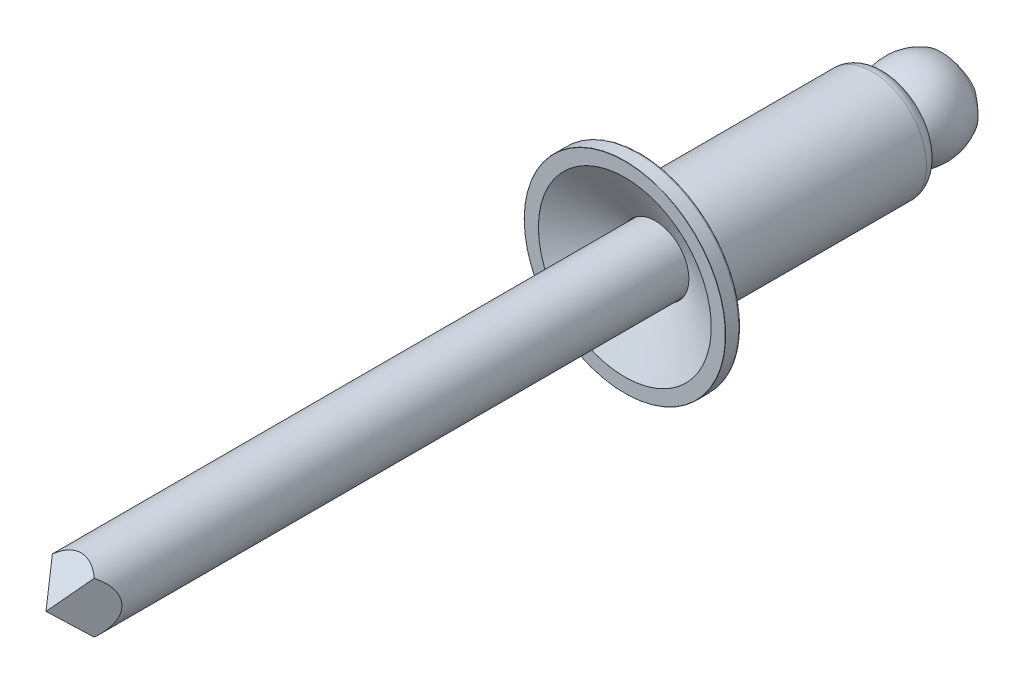
SolidWorks part; units mm, degrees
ref_plane "Front" through (0, 0, 0) normal (0, 0, 1) x (1, 0, 0)
ref_plane "Top" through (0, 0, 0) normal (0, 1, 0) x (1, 0, 0)
ref_plane "Right" through (0, 0, 0) normal (1, 0, 0) x (0, 0, -1)
sketch "Sketch1" plane through (0, 0, 0) normal (1, 0, 0) x (0, 0, -1)
  line L0 (-27.2034, 0) -> (-1.8034, 0) construction
  line L1 (-1.8034, 0) -> (0, 0) construction
  line L2 (0, 0) -> (9.6266, 0) construction
  line L3 (9.6266, 0) -> (12.4841, 0) construction
  line L4 (-1.1768, 4.4196) -> (0, 2.3813) construction
  line L5 (0, -2.3813) -> (-1.1768, -4.4196) construction
  line L8 (0, 4.4196) -> (0, -4.4196) construction
  line L9 (9.6266, 2.3813) -> (9.6266, -2.3813) construction
  point P7 (-1.8034, 4.4196)
  point P10 (-1.8034, -4.4196)
  point P25 (-1.8034, 1.4478)
  dimension "Head Height" = 1.8034
  dimension "D5" = 2.8575
  dimension "Diameter" = 4.7625
  dimension "Head Diameter" = 8.8392
  dimension "Countersink Angle" = 120
  dimension "Mandrel OD" = 2.8956
  dimension "Length" = 11.43
sketch "Sketch2" plane through (0, 0, 0) normal (1, 0, 0) x (0, 0, -1)
  line L0 (-27.2034, 0) -> (-27.2034, 1.4478)
  line L1 (-1.8034, 4.4196) -> (-1.8034, 3.793)
  line L2 (-1.8034, 4.4196) -> (-1.1768, 4.4196)
  line L3 (0, 0) -> (0, 4.4196) construction
  line L4 (-1.8034, 0) -> (-1.8034, 0.7239) construction
  line L5 (9.0551, 2.3812) -> (0, 2.3812)
  line L6 (9.6266, 2.3813) -> (9.6266, -2.3813) construction
  line L7 (-1.1768, 4.4196) -> (0, 2.3813) construction
  line L8 (0, 0) -> (9.6266, 0) construction
  line L9 (9.6266, 1.905) -> (12.4841, 1.905) construction
  line L10 (9.6266, 1.6669) -> (9.4075, 1.4478)
  line L11 (9.4075, 1.4478) -> (9.6266, 1.4478)
  line L12 (-27.2034, 0) -> (9.6266, 0)
  line L13 (-1.8034, 1.4478) -> (-1.8034, 0) construction
  line L14 (9.6266, 1.4478) -> (9.6266, 1.905) construction
  line L15 (12.4841, 0) -> (12.4841, 1.905) construction
  line L16 (12.076, 1.6193) -> (12.4841, 1.905) construction
  line L17 (-0.464, 1.4732) -> (4.5275, 1.4732)
  line L18 (12.076, 1.6193) -> (12.076, 0)
  line L19 (-1.1768, 4.4196) -> (0, 2.3812)
  line L20 (-1.8034, 1.4478) -> (-27.2034, 1.4478)
  line L21 (4.5275, 1.4732) -> (4.5275, 1.4478)
  line L22 (4.5275, 1.4478) -> (-1.8034, 1.4478)
  line L23 (12.076, 0) -> (9.6266, 0)
  line L24 (-1.8034, 3.793) -> (-0.464, 1.4732)
  arc A0 (9.0551, 2.3812) -> (9.6266, 1.6669) centre (9.0551, 1.7955) cw
  arc A1 (9.6266, 1.4478) -> (12.076, 1.6193) centre (10.9819, -0.3324) cw
  arc A2 (12.076, 1.6193) -> (12.4841, 0) centre (9.0676, 0) cw construction
  point P39 (4.5275, 2.3812)
  dimension "D1" = 0.5715
  dimension "D2" = 45
  dimension "D3" = 3.3337
  dimension "D4" = 3.81
  dimension "D5" = 35
  dimension "D6" = 3.2385
  dimension "D7" = 0.0254
revolve "Revolve1" add sketch "Sketch2" angle 360 about L12
sketch "Sketch3" plane through (0, 0, 0) normal (0, 1, 0) x (1, 0, 0)
  line L0 (0, -27.2034) -> (1.651, -25.0518)
  line L1 (-1.4478, -27.2034) -> (1.4478, -27.2034) construction
  line L3 (0, -27.2034) -> (0, -27.7114) construction
  line L4 (0, -27.2034) -> (-1.651, -25.0518)
  line L5 (-1.651, -25.0518) -> (-1.651, -27.7114)
  line L6 (-1.651, -27.7114) -> (1.651, -27.7114)
  line L7 (1.651, -27.7114) -> (1.651, -25.0518)
  dimension "D1" = 75
  dimension "D2" = 0.2032
  dimension "D3" = 0.508
extrude "Cut-Extrude1" cut sketch "Sketch3" against normal through all both and the other way through all
sketch "Sketch5" plane through (0, 0, 0) normal (1, 0, 0) x (0, 0, -1)
  line L0 (-27.2034, 0) -> (-25.3166, 1.7653)
  line L1 (-27.2034, -1.4478) -> (-27.2034, 1.4478) construction
  line L2 (-25.3166, 1.7653) -> (-27.5209, 1.7653)
  line L3 (-27.5209, 1.7653) -> (-27.5209, -1.7653)
  line L4 (-27.5209, -1.7653) -> (-25.3166, -1.7653)
  line L5 (-25.3166, -1.7653) -> (-27.2034, 0)
  line L6 (-27.2034, 0) -> (-9.2614, 0) construction
  line L7 (4.5276, 1.4478) -> (-27.2034, 1.4478) construction
  line L8 (-25.3166, 0) -> (-25.3166, 1.7653) construction
  ellipse E0 centre (-27.2034, 0) end of major axis (-29.0902, 0) minor radius 1.4478 (-27.2034, -1.4478) -> (-27.2034, 1.4478) ccw construction
  dimension "D1" = 0.3175
  dimension "D2" = 0.3175
extrude "Cut-Extrude2" cut sketch "Sketch5" against normal through all both and the other way through all
sketch "Sketch10" plane through (0, 0, 0) normal (1, 0, 0) x (0, 0, -1)
  line L6 (12.076, 1.6193) -> (12.4841, 0)
  line L7 (12.4841, 0) -> (12.076, -1.6193)
  line L8 (12.076, -1.6193) -> (12.076, 1.6193)
extrude "Boss-Extrude1" add sketch "Sketch10" along normal mid plane 3.81
sketch "Sketch12" plane through (0, 0, 0) normal (0, 1, 0) x (1, 0, 0)
  line L0 (1.905, 12.4841) -> (-1.905, 12.4841) construction
  line L1 (-0.9226, 12.4841) -> (-0.9226, 15.9811)
  line L2 (-0.9226, 15.9811) -> (-4.4196, 15.9811)
  line L3 (-4.4196, 15.9811) -> (-4.4196, 9.6266)
  line L4 (-4.4196, 9.6266) -> (-1.4478, 9.6266)
  line L10 (-4.4196, -1.1768) -> (-4.4196, -1.8034) construction
  arc A0 (-1.6192, 12.076) -> (-1.4478, 9.6266) centre (0.3324, 10.9819) ccw
  arc A1 (0.9652, 11.7348) -> (1.147, 13.3888) centre (-0.0003, 12.6779) ccw
  arc A3 (-1.6192, 12.076) -> (-1.4478, 9.6266) centre (0.3324, 10.9819) ccw
  arc A4 (-1.6192, 12.076) -> (-0.9226, 12.4841) centre (-0.9226, 11.6855) cw
revolve "Cut-Revolve1" cut sketch "Sketch12" angle 360 about L2
sketch "Sketch13" plane through (0, 0, 0) normal (0, 1, 0) x (1, 0, 0)
  line L0 (-0.9226, 12.4841) -> (-1.6192, 12.076)
  line L1 (-1.6192, 12.076) -> (-1.6192, 15.9811)
  line L2 (-1.6192, 15.9811) -> (-0.9226, 15.9811)
  line L3 (-0.9226, 15.9811) -> (-0.9226, 12.4841)
  line L4 (-0.9226, 15.9811) -> (-4.4196, 15.9811) construction
  line L5 (0, 0) -> (0, 15.9811) construction
  line L6 (1.6192, 12.076) -> (1.6192, 15.9811)
  line L7 (0.9226, 12.4841) -> (1.6192, 12.076)
  line L8 (0.9226, 15.9811) -> (0.9226, 12.4841)
  line L9 (1.6192, 15.9811) -> (0.9226, 15.9811)
extrude "Cut-Extrude6" cut sketch "Sketch13" against normal through all both and the other way through all
fillet "Fillet1" radius 0.0902 2 edges at (4.4196, 0, 1.1768) (2.3812, 0, 0)
fillet "Fillet2" radius 0.009 2 edges at (3.793, 0, 1.8034) (4.4196, 0, 1.8034)
equation "\"D5@Sketch1\"=\"Diameter@Sketch1\"*0.6"
equation "\"D2@Sketch5\"=\"D1@Sketch5\""
equation "\"D1@Sketch2\"=\"Length@Sketch1\"*0.05"
equation "\"D3@Sketch2\"=\"Diameter@Sketch1\"*0.7"
equation "\"D4@Sketch2\"=\"Diameter@Sketch1\"*0.8"
equation "\"D6@Sketch2\"=\"D4@Sketch2\"*0.85"
equation "\"D1@Boss-Extrude1\"=\"D4@Sketch2\""
equation "\"D1@Fillet1\"=\"Head Height@Sketch1\"*0.05"
equation "\"D1@Fillet2\"=\"D1@Fillet1\"*0.1"
